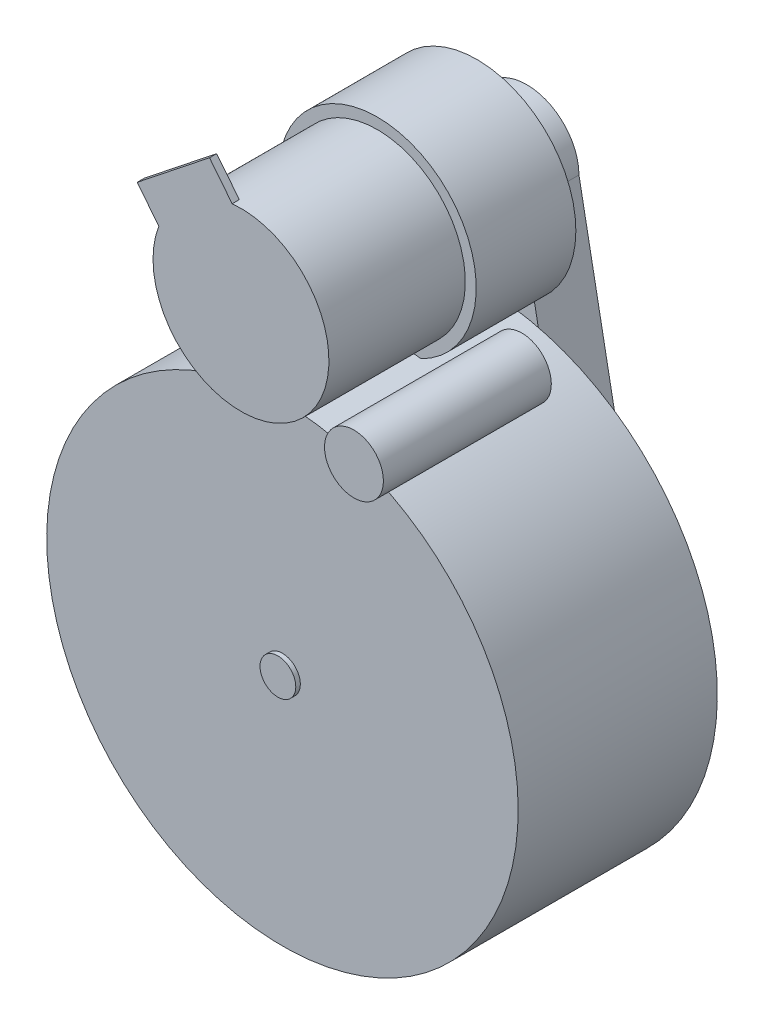
SolidWorks part; units mm, degrees
ref_plane "Front Plane" through (0, 0, 0) normal (0, 0, 1) x (1, 0, 0)
ref_plane "Top Plane" through (0, 0, 0) normal (0, 1, 0) x (1, 0, 0)
ref_plane "Right Plane" through (0, 0, 0) normal (1, 0, 0) x (0, 0, -1)
sketch "Sketch1" plane through (0, 0, 0) normal (0, 0, 1) x (1, 0, 0)
  circle A0 centre (0, 0) radius 36.83
  dimension "D1" = 73.66
extrude "Boss-Extrude1" add sketch "Sketch1" along normal blind 31.115
sketch "Sketch2" plane through (0, 0, 0) normal (0, 0, -1) x (-1, 0, 0)
  circle A0 centre (0, 0) radius 24
extrude "Boss-Extrude2" add sketch "Sketch2" along normal blind 4.318
sketch "Sketch5" plane through (0, 0, 31.115) normal (0, 0, 1) x (1, 0, 0)
  circle A0 centre (0, 0) radius 2.794
  dimension "D1" = 5.588
extrude "Boss-Extrude5" add sketch "Sketch5" along normal blind 0.7112
sketch "Sketch14" plane through (0, 0, -4.318) normal (0, 0, -1) x (-1, 0, 0)
  circle A0 centre (0, 0) radius 15.6337
  dimension "D1" = 31.2674
extrude "Boss-Extrude11" add sketch "Sketch14" along normal blind 4.8514
sketch "Sketch15" plane through (0, 0, -9.1694) normal (0, 0, -1) x (-1, 0, 0)
  circle A0 centre (0, 0) radius 12.8016
  dimension "D1" = 25.6032
extrude "Boss-Extrude12" add sketch "Sketch15" along normal blind 5.2832
sketch "Sketch16" plane through (0, 0, -14.4526) normal (0, 0, -1) x (-1, 0, 0)
  circle A0 centre (0, 0) radius 2.7686
  dimension "D1" = 5.5372
extrude "Boss-Extrude13" add sketch "Sketch16" along normal blind 0.7112
sketch "Sketch17" plane through (0, 0, -9.1694) normal (0, 0, -1) x (-1, 0, 0)
  line L0 (2.1102, 58.5343) -> (0, -15.6337) construction
  circle A0 centre (2.1102, 50.3809) radius 8.1534
  circle A1 centre (0, 0) radius 15.6337 construction
  dimension "D1" = 16.3068
  dimension "D2" = 74.168
extrude "Boss-Extrude14" add sketch "Sketch17" against normal blind 7.7724 separate body
sketch "Sketch18" plane through (0, 0, -1.397) normal (0, 0, 1) x (1, 0, 0)
  circle A0 centre (-2.1102, 50.3809) radius 15.4432
  dimension "D1" = 30.8864
extrude "Boss-Extrude15" add sketch "Sketch18" along normal blind 15.5702
sketch "Sketch19" plane through (0, 0, 14.1732) normal (0, 0, 1) x (1, 0, 0)
  circle A0 centre (-2.1102, 50.3809) radius 13.7414
  dimension "D1" = 27.4828
extrude "Boss-Extrude16" add sketch "Sketch19" along normal blind 21.3106
sketch "Sketch22" plane through (0, 0, -9.1694) normal (0, 0, -1) x (-1, 0, 0)
sketch "Sketch23" plane through (0, 0, -9.1694) normal (0, 0, -1) x (-1, 0, 0)
  line L0 (15.6337, 0) -> (10.2636, 50.3809)
  line L1 (-15.6337, 0) -> (-6.0432, 50.3809)
  line L2 (-6.0432, 50.3809) -> (10.2636, 50.3809)
  line L3 (-15.6337, 0) -> (15.6337, 0)
  circle A0 centre (0, 0) radius 15.6337 construction
  circle A1 centre (2.1102, 50.3809) radius 8.1534 construction
extrude "Boss-Extrude17" add sketch "Sketch23" against normal blind 9.144
sketch "Sketch24" plane through (0, 0, -9.1694) normal (0, 0, -1) x (-1, 0, 0)
  circle A0 centre (2.1102, 50.3809) radius 2.4892
  dimension "D1" = 4.9784
extrude "Boss-Extrude18" add sketch "Sketch24" along normal blind 1.9812
sketch "Sketch25" plane through (0, 0, -9.1694) normal (0, 0, -1) x (-1, 0, 0)
  line L0 (2.1102, 50.3809) -> (0, 0) construction
  line L1 (2.1102, 50.3809) -> (1.633, 38.9863) construction
  circle A0 centre (1.633, 38.9863) radius 3.2258
  dimension "D2" = 6.4516
  dimension "D1" = 11.4046
extrude "Boss-Extrude19" add sketch "Sketch25" along normal blind 3.048
sketch "Sketch27" plane through (0, 0, 35.4838) normal (0, 0, 1) x (1, 0, 0)
  line L0 (32.1663, 18.6462) -> (9.65, 57.4889) construction
  line L1 (-2.1102, 50.3809) -> (19.9099, 39.7897) construction
  line L2 (19.9099, 39.7897) -> (15.5411, 38.3569) construction
  circle A0 centre (0, 0) radius 37.18 construction
  circle A2 centre (-2.1102, 50.3809) radius 13.7414 construction
  circle A3 centre (15.5411, 38.3569) radius 4.5977
  dimension "D1" = 24.4348
  dimension "D2" = 4.3688
extrude "Boss-Extrude20" add sketch "Sketch27" against normal blind 26.2382
sketch "Sketch29" plane through (0, 0, 35.4838) normal (0, 0, 1) x (1, 0, 0)
  line L0 (-3.4869, 64.0532) -> (-7.0247, 68.5091)
  line L1 (-7.0247, 68.5091) -> (-18.3237, 59.5381)
  line L2 (-18.3237, 59.5381) -> (-14.9468, 55.2849)
  line L3 (-14.9468, 55.2849) -> (-3.4869, 64.0532)
  line L4 (-7.0247, 68.5091) -> (-14.9468, 55.2849) construction
  line L5 (-3.4869, 64.0532) -> (-18.3237, 59.5381) construction
  line L6 (-2.1102, 50.3809) -> (-10.9857, 61.897) construction
  line L7 (-14.372, 44.1781) -> (9.9763, 56.9187) construction
  circle A0 centre (-2.1102, 50.3809) radius 13.7414 construction
  circle A1 centre (-2.1102, 50.3809) radius 13.7414 construction
  dimension "D1" = 14.4272
  dimension "D2" = 5.6896
  dimension "D3" = 80
extrude "Boss-Extrude21" add sketch "Sketch29" against normal blind 1.1176
sketch "Sketch31" plane through (0, 0, 31.115) normal (0, 0, 1) x (1, 0, 0)
  line L1 (32.6197, 17.0999) -> (-17.8338, -9.3629) construction
  line L2 (-17.8338, -9.3629) -> (0, 0) construction
  line L3 (-17.8338, -9.3629) -> (0, 0) construction
  line L4 (-17.8338, -9.3629) -> (-12.8525, -18.8826)
  line L5 (-17.8338, -9.3629) -> (-22.7899, 0.1699)
  arc A0 (-3.2469, 36.6866) -> (14.3709, 33.9106) centre (0, 0) ccw construction
  dimension "D1" = 20.1422
  dimension "D2" = 10.7442
  dimension "D3" = 10.7442
